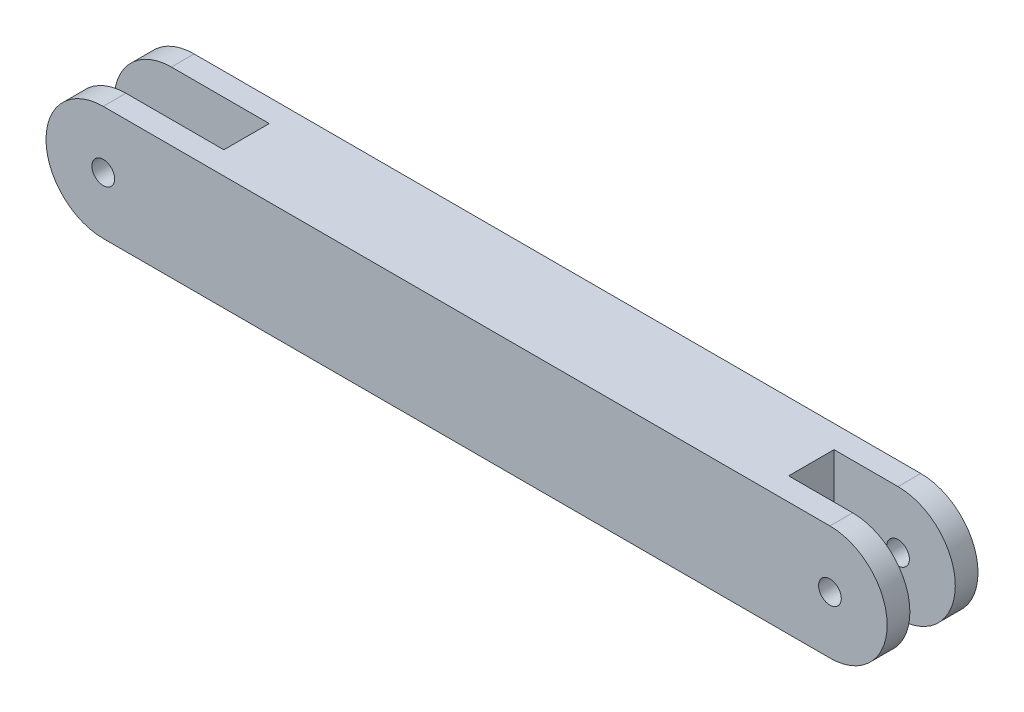
SolidWorks part; units mm, degrees
ref_plane "Front" through (0, 0, 0) normal (0, 0, 1) x (1, 0, 0)
ref_plane "Top" through (0, 0, 0) normal (0, 1, 0) x (1, 0, 0)
ref_plane "Right" through (0, 0, 0) normal (1, 0, 0) x (0, 0, -1)
sketch "Sketch1" plane through (0, 0, 0) normal (0, 0, 1) x (1, 0, 0)
  line L0 (-47.2174, -8.0781) -> (155.9826, -8.0781) construction
  line L1 (-47.2174, 7.9239) -> (155.9826, 7.9239)
  line L2 (-47.2174, -24.0801) -> (155.9826, -24.0801)
  arc A0 (-47.2174, 7.9239) -> (-47.2174, -24.0801) centre (-47.2174, -8.0781) ccw
  arc A1 (155.9826, -24.0801) -> (155.9826, 7.9239) centre (155.9826, -8.0781) ccw
  circle A2 centre (-47.2174, -8.0781) radius 3.175
  circle A3 centre (155.9826, -8.0781) radius 3.175
  point P2 (54.3826, -8.0781)
  dimension "D1" = 16.002
  dimension "D3" = 6.35
  dimension "D4" = 6.35
  dimension "D2" = 203.2
extrude "Boss-Extrude1" add sketch "Sketch1" along normal blind 6.35
sketch "Sketch2" plane through (0, 0, 6.35) normal (0, 0, 1) x (1, 0, 0)
  line L2 (-29.9926, -24.0801) -> (-29.9926, 7.9239)
  line L4 (155.9826, 7.9239) -> (-47.2174, 7.9239) construction
  line L7 (-47.2174, -24.0801) -> (155.9826, -24.0801) construction
  line L9 (138.0826, -24.0801) -> (138.0826, 7.9239)
  line L10 (-29.9926, 7.9239) -> (138.0826, 7.9239)
  line L11 (-29.9926, -24.0801) -> (138.0826, -24.0801)
  point P13 (-29.9926, -8.0781)
  point P16 (16.9972, 0.4239)
  point P24 (138.0826, -8.0781)
extrude "Boss-Extrude2" add sketch "Sketch2" along normal blind 12.7
sketch "Sketch5" plane through (0, 0, 19.05) normal (0, 0, 1) x (1, 0, 0)
  line L0 (-47.2174, -8.0781) -> (155.9826, -8.0781) construction
  line L1 (-47.2174, 7.9239) -> (155.9826, 7.9239)
  line L2 (-47.2174, -24.0801) -> (155.9826, -24.0801)
  arc A0 (-47.2174, 7.9239) -> (-47.2174, -24.0801) centre (-47.2174, -8.0781) ccw
  arc A1 (155.9826, -24.0801) -> (155.9826, 7.9239) centre (155.9826, -8.0781) ccw
  circle A2 centre (-47.2174, -8.0781) radius 3.175
  circle A3 centre (155.9826, -8.0781) radius 3.175
  point P4 (54.3826, -8.0781)
  dimension "D1" = 16.002
  dimension "D2" = 6.35
  dimension "D3" = 6.35
extrude "Boss-Extrude3" add sketch "Sketch5" along normal blind 6.35
sketch "Sketch7" plane through (-29.9926, 0, 0) normal (-1, 0, 0) x (0, 0, 1)
  line L1 (6.35, 7.9239) -> (19.05, 7.9239)
  line L2 (6.35, 7.9239) -> (6.35, -24.0801)
  line L3 (6.35, -24.0801) -> (19.05, -24.0801)
  line L4 (19.05, 7.9239) -> (19.05, -24.0801)
extrude "Cut-Extrude1" cut sketch "Sketch7" against normal blind 10.16
